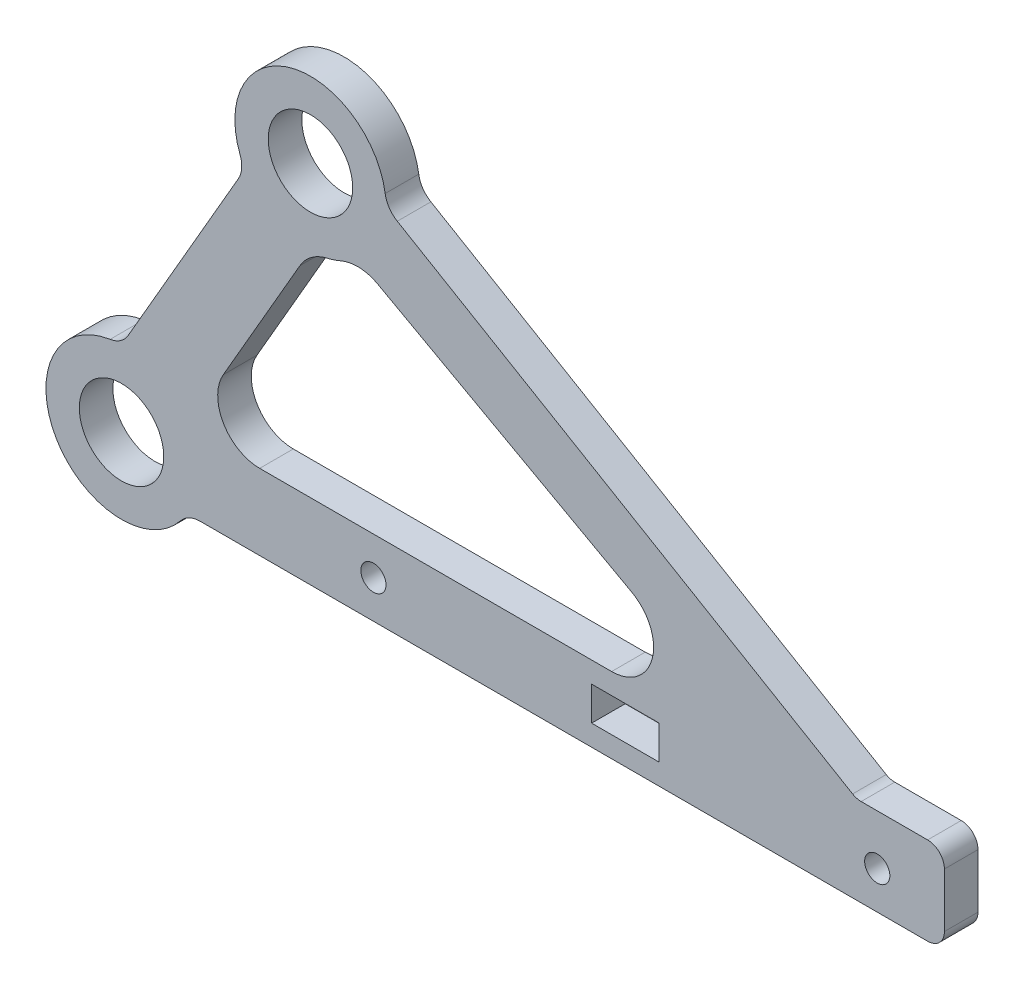
SolidWorks part; units mm, degrees
ref_plane "前视基准面" through (0, 0, 0) normal (0, 0, 1) x (1, 0, 0)
ref_plane "上视基准面" through (0, 0, 0) normal (0, 1, 0) x (1, 0, 0)
ref_plane "右视基准面" through (0, 0, 0) normal (1, 0, 0) x (0, 0, -1)
sketch "草图1" plane through (0, 0, 0) normal (0, 0, 1) x (1, 0, 0)
  line L1 (0, 0) -> (22.5, 38.9711) construction
  line L6 (0, 0) -> (30, 0) construction
  line L7 (90, 0) -> (60, 0) construction
  line L8 (87, -4.5) -> (9.3675, -4.5)
  line L9 (55.985, 2.015) -> (64.015, 2.015)
  line L10 (55.985, 2.015) -> (55.985, -2.015)
  line L11 (55.985, -2.015) -> (64.015, -2.015)
  line L12 (64.015, 2.015) -> (64.015, -2.015)
  line L13 (55.985, 2.015) -> (64.015, -2.015) construction
  line L14 (55.985, -2.015) -> (64.015, 2.015) construction
  line L16 (0.7866, 10.3625) -> (13.9191, 33.1087)
  line L17 (21.2554, 27.8154) -> (12.1244, 12)
  line L20 (30.5219, 30.5259) -> (60.7776, 13.8808)
  line L21 (32.8422, 38.1803) -> (87.0684, 6.2274)
  line L22 (16.4545, 4.5) -> (58.3675, 4.5)
  line L23 (90, 0) -> (98, 0) construction
  line L24 (98, 0) -> (98, -2.5)
  line L25 (96, -4.5) -> (87, -4.5)
  line L26 (88.0838, 5.9505) -> (96, 5.9505)
  line L27 (98, 3.9505) -> (98, 0)
  circle A0 centre (0, 0) radius 5.03
  circle A1 centre (22.5, 38.9711) radius 5.03
  circle A2 centre (0, 0) radius 9 construction
  circle A4 centre (22.5, 38.9711) radius 9 construction
  circle A6 centre (30, 0) radius 1.5
  arc A7 (-1.3586, 8.8969) -> (7.0256, -5.625) centre (0, 0) ccw
  arc A9 (14.1158, 35.6993) -> (31.3989, 40.3165) centre (22.5, 38.9711) cw
  arc A10 (24.4835, 30.1924) -> (26.1076, 30.7258) centre (22.5, 38.9711) ccw
  arc A11 (58.3675, 4.5) -> (60.7776, 13.8808) centre (58.3675, 9.5) ccw
  arc A12 (30.5219, 30.5259) -> (26.1076, 30.7258) centre (28.1118, 26.1451) ccw
  arc A13 (24.4835, 30.1924) -> (21.2554, 27.8154) centre (25.5855, 25.3154) ccw
  arc A14 (12.1244, 12) -> (16.4545, 4.5) centre (16.4545, 9.5) ccw
  arc A17 (9.3675, -4.5) -> (7.0256, -5.625) centre (9.3675, -7.5) ccw
  arc A18 (-1.3586, 8.8969) -> (0.7866, 10.3625) centre (-1.8114, 11.8625) ccw
  arc A19 (13.9191, 33.1087) -> (14.1158, 35.6993) centre (11.3211, 34.6087) ccw
  arc A20 (32.8422, 38.1803) -> (31.3989, 40.3165) centre (34.3652, 40.7649) cw
  circle A21 centre (90, 0) radius 1.5
  arc A22 (87.0684, 6.2274) -> (88.0838, 5.9505) centre (88.0838, 7.9505) ccw
  arc A23 (96, -4.5) -> (98, -2.5) centre (96, -2.5) ccw
  arc A24 (98, 3.9505) -> (96, 5.9505) centre (96, 3.9505) ccw
  point P35 (22.5, 29.9711)
  point P38 (7.7942, 4.5)
  point P45 (7.7942, -4.5)
  point P48 (0, 9)
  point P51 (14.7058, 34.4711)
  dimension "D1" = 2
  dimension "D2" = 5
  dimension "D5" = 3
  dimension "D6" = 30
extrude "凸台-拉伸1" add sketch "草图1" along normal blind 4
